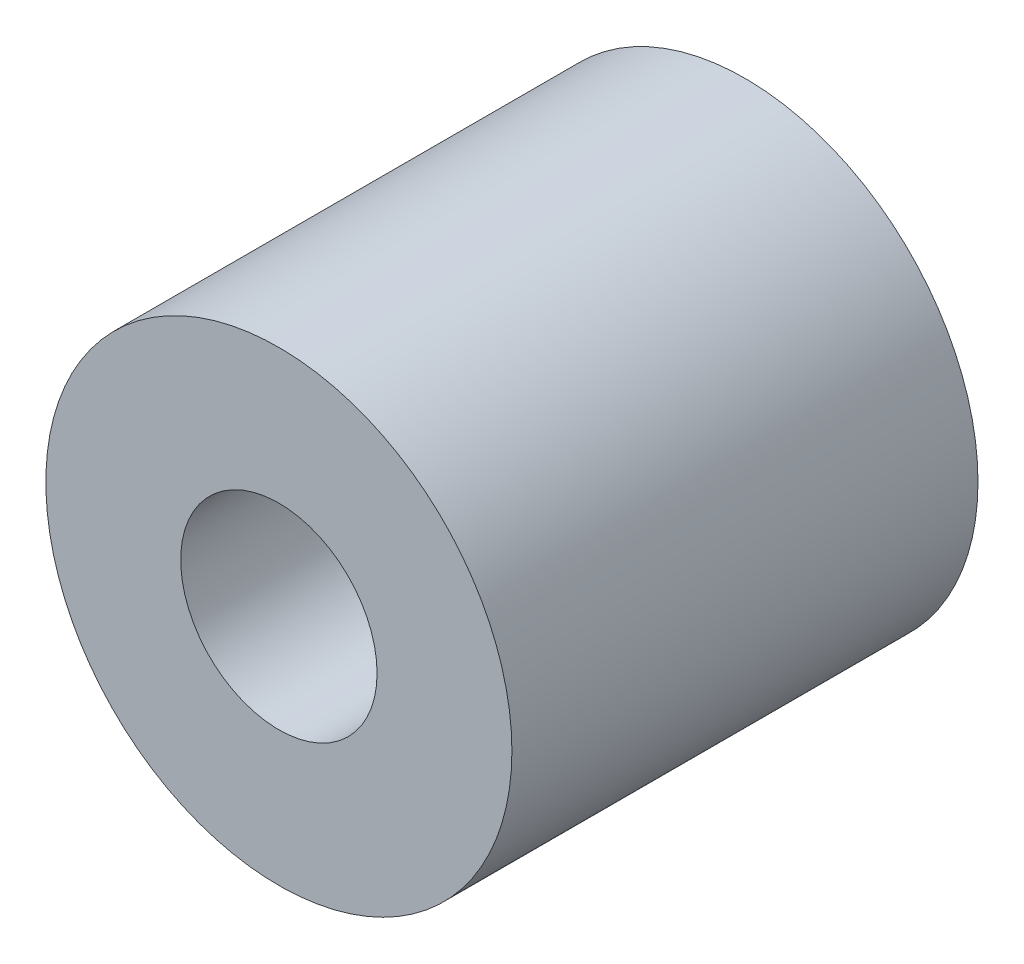
SolidWorks part; units mm, degrees
ref_plane "Front Plane" through (0, 0, 0) normal (0, 0, 1) x (1, 0, 0)
ref_plane "Top Plane" through (0, 0, 0) normal (0, 1, 0) x (1, 0, 0)
ref_plane "Right Plane" through (0, 0, 0) normal (1, 0, 0) x (0, 0, -1)
sketch "Sketch1" plane through (0, 0, 0) normal (0, 0, 1) x (1, 0, 0)
  circle A0 centre (113.0054, -113.0054) radius 7.5
  dimension "D1" = 15
extrude "Boss-Extrude1" add sketch "Sketch1" along normal blind 15 contours A0
sketch "Sketch2" plane through (0, 0, 15) normal (0, 0, 1) x (1, 0, 0)
  circle A0 centre (113.0054, -113.0054) radius 3.16
extrude "Cut-Extrude1" cut sketch "Sketch2" against normal blind 15
